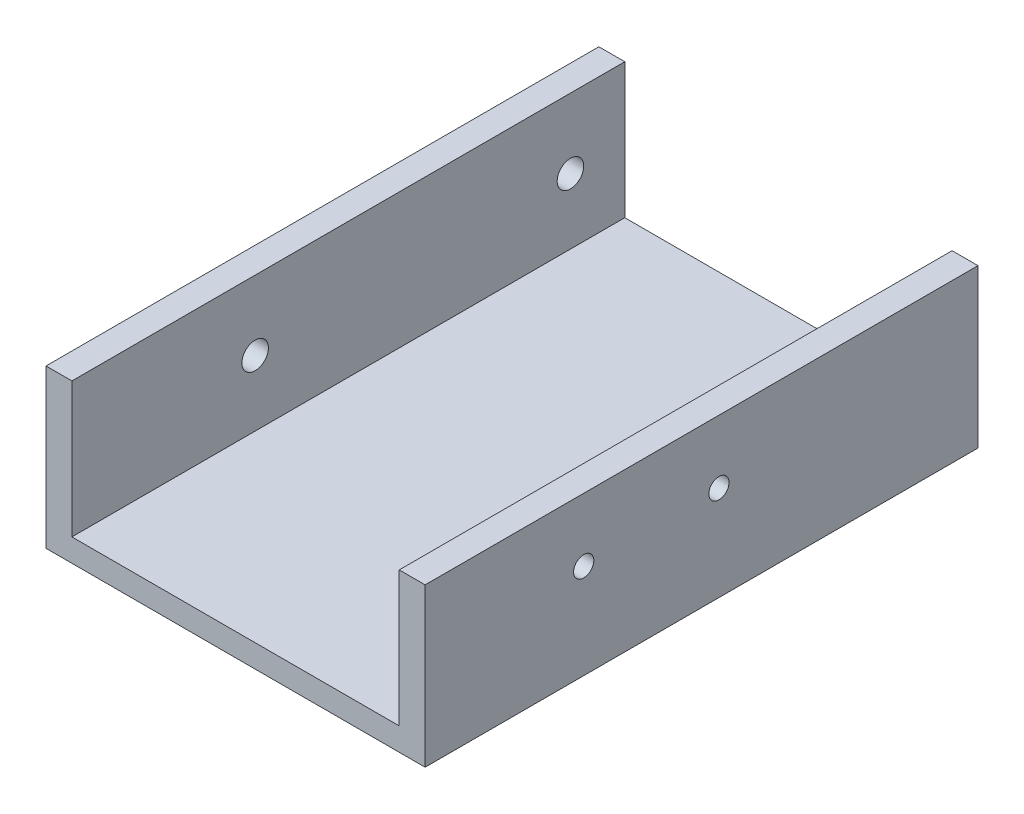
SolidWorks part; units mm, degrees
material "6061 Alloy"
ref_plane "Front Plane" through (0, 0, 0) normal (0, 0, 1) x (1, 0, 0)
ref_plane "Top Plane" through (0, 0, 0) normal (0, 1, 0) x (1, 0, 0)
ref_plane "Right Plane" through (0, 0, 0) normal (1, 0, 0) x (0, 0, -1)
sketch "Sketch2" plane through (0, 0, 0) normal (0, 0, 1) x (1, 0, 0)
  line L0 (-38.1, 0) -> (38.1, 0)
  line L1 (-38.1, 0) -> (-38.1, 31.75)
  line L2 (-38.1, 31.75) -> (-32.893, 31.75)
  line L3 (-32.893, 31.75) -> (-32.893, 4.5974)
  line L4 (-32.893, 4.5974) -> (32.893, 4.5974)
  line L5 (32.893, 4.5974) -> (32.893, 31.75)
  line L6 (32.893, 31.75) -> (38.1, 31.75)
  line L7 (38.1, 31.75) -> (38.1, 0)
  point P8 (0, 4.5974)
  point P10 (0, 0)
  point P11 (35.4965, 31.75)
  dimension "D1" = 5.207
  dimension "D2" = 31.75
  dimension "D3" = 76.2
  dimension "D4" = 31.75
extrude "Boss-Extrude3" add sketch "Sketch2" along normal blind 111.125
sketch "Sketch4" plane through (-32.893, 0, 0) normal (1, 0, 0) x (0, 0, -1)
  line L0 (0, 4.5974) -> (0, 31.75) construction
  circle A0 centre (-10.922, 17.7352) radius 2.667
  dimension "D1" = 10.922
  dimension "D2" = 5.334
extrude "Cut-Extrude1" cut sketch "Sketch4" against normal through all
sketch "Sketch5" plane through (-32.893, 0, 0) normal (1, 0, 0) x (0, 0, -1)
  line L0 (-111.125, 31.75) -> (0, 31.75) construction
  line L1 (-111.125, 4.5974) -> (-111.125, 31.75) construction
  circle A0 centre (-74.295, 17.78) radius 2.667
  dimension "D1" = 36.83
  dimension "D2" = 5.334
  dimension "D3" = 13.97
extrude "Cut-Extrude2" cut sketch "Sketch5" against normal through all
sketch "Sketch6" plane through (32.893, 0, 0) normal (-1, 0, 0) x (0, 0, 1)
  line L0 (0, 31.75) -> (0, 4.5974) construction
  line L1 (111.125, 31.75) -> (0, 31.75) construction
  circle A0 centre (52.07, 19.05) radius 2.032
  dimension "D1" = 52.07
  dimension "D2" = 12.7
  dimension "D3" = 4.064
extrude "Cut-Extrude3" cut sketch "Sketch6" against normal through all
sketch "Sketch7" plane through (32.893, 0, 0) normal (-1, 0, 0) x (0, 0, 1)
  line L0 (0, 31.75) -> (0, 4.5974) construction
  line L1 (111.125, 31.75) -> (0, 31.75) construction
  circle A0 centre (79.248, 19.05) radius 2.032
  dimension "D1" = 79.248
  dimension "D2" = 12.7
  dimension "D3" = 4.064
extrude "Cut-Extrude4" cut sketch "Sketch7" against normal through all
